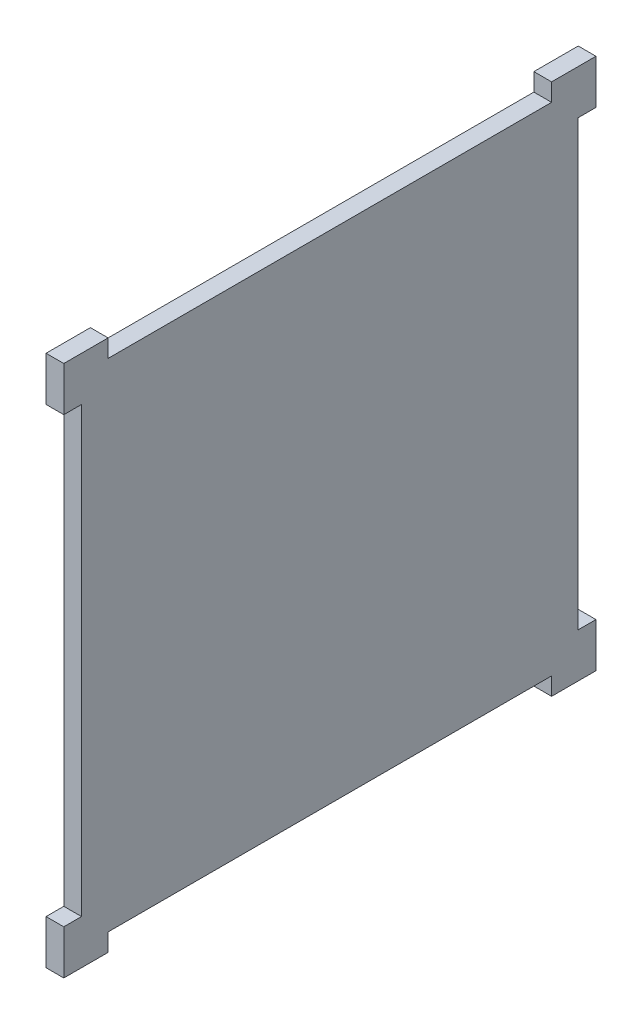
SolidWorks part; units mm, degrees
ref_plane "Front Plane" through (0, 0, 0) normal (0, 0, 1) x (1, 0, 0)
ref_plane "Top Plane" through (0, 0, 0) normal (0, 1, 0) x (1, 0, 0)
ref_plane "Right Plane" through (0, 0, 0) normal (1, 0, 0) x (0, 0, -1)
sketch "Sketch1" plane through (0, 0, 0) normal (1, 0, 0) x (0, 0, -1)
  line L0 (-63.5, 71.12) -> (63.5, 71.12)
  line L1 (-76.2, -76.2) -> (-63.5, -76.2)
  line L2 (-76.2, -76.2) -> (-76.2, -63.5)
  line L3 (-76.2, 76.2) -> (-63.5, 76.2)
  line L4 (76.2, -76.2) -> (76.2, -63.5)
  line L7 (71.12, -63.5) -> (71.12, 63.5)
  line L8 (-63.5, -71.12) -> (63.5, -71.12)
  line L9 (-71.12, -63.5) -> (-71.12, 63.5)
  line L10 (-63.5, 76.2) -> (-63.5, 71.12)
  line L11 (-76.2, 63.5) -> (-71.12, 63.5)
  line L12 (63.5, -76.2) -> (63.5, -71.12)
  line L13 (76.2, -63.5) -> (71.12, -63.5)
  line L15 (-63.5, -76.2) -> (-63.5, -71.12)
  line L16 (-76.2, -63.5) -> (-71.12, -63.5)
  line L17 (63.5, 76.2) -> (63.5, 71.12)
  line L18 (76.2, 63.5) -> (71.12, 63.5)
  line L19 (63.5, 76.2) -> (76.2, 76.2)
  line L20 (-76.2, 63.5) -> (-76.2, 76.2)
  line L21 (-76.2, 76.2) -> (76.2, 76.2) construction
  line L22 (-71.12, 71.12) -> (71.12, 71.12) construction
  line L23 (-71.12, -71.12) -> (-71.12, 71.12) construction
  line L24 (63.5, -76.2) -> (76.2, -76.2)
  line L25 (-76.2, -76.2) -> (-76.2, 76.2) construction
  line L26 (76.2, 63.5) -> (76.2, 76.2)
  line L27 (-76.2, -76.2) -> (76.2, -76.2) construction
  line L29 (76.2, -76.2) -> (76.2, 76.2) construction
  line L30 (71.12, -71.12) -> (71.12, 71.12) construction
  line L31 (-71.12, -71.12) -> (71.12, -71.12) construction
  point P0 (0, 0)
  dimension "D1" = 152.4
  dimension "D2" = 152.4
  dimension "D3" = 5.08
  dimension "D4" = 12.7
extrude "Boss-Extrude1" add sketch "Sketch1" along normal blind 5.08
